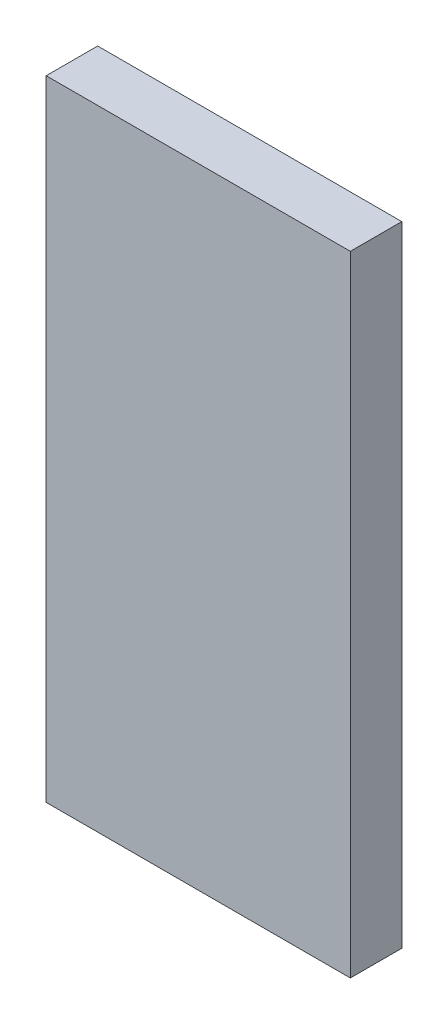
SolidWorks part; units mm, degrees
ref_plane "Plano frontal" through (0, 0, 0) normal (0, 0, 1) x (1, 0, 0)
ref_plane "Plano superior" through (0, 0, 0) normal (0, 1, 0) x (1, 0, 0)
ref_plane "Plano direito" through (0, 0, 0) normal (1, 0, 0) x (0, 0, -1)
sketch "Sketch1" plane through (0, 0, 0) normal (0, 0, 1) x (1, 0, 0)
  line L1 (-6.5, -13.45) -> (6.5, -13.45)
  line L2 (-6.5, -13.45) -> (-6.5, 13.45)
  line L3 (-6.5, 13.45) -> (6.5, 13.45)
  line L4 (6.5, -13.45) -> (6.5, 13.45)
  line L5 (-6.5, -13.45) -> (6.5, 13.45) construction
  line L6 (-6.5, 13.45) -> (6.5, -13.45) construction
  point P0 (0, 0)
  dimension "D1" = 13
  dimension "D2" = 26.9
extrude "Boss-Extrude1" add sketch "Sketch1" along normal mid plane 2.2
